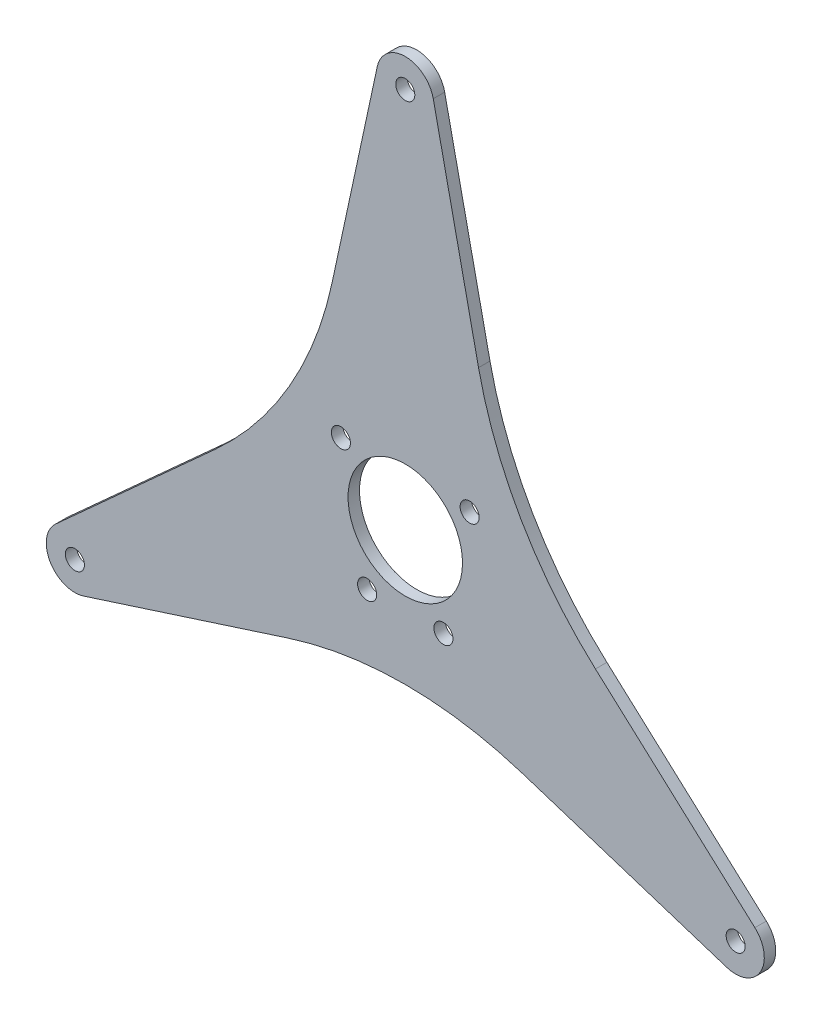
SolidWorks part; units mm, degrees
ref_plane "Front Plane" through (0, 0, 0) normal (0, 0, 1) x (1, 0, 0)
ref_plane "Top Plane" through (0, 0, 0) normal (0, 1, 0) x (1, 0, 0)
ref_plane "Right Plane" through (0, 0, 0) normal (1, 0, 0) x (0, 0, -1)
sketch "Sketch1" plane through (0, 0, 0) normal (0, 0, 1) x (1, 0, 0)
  line L0 (33.75, 25.0611) -> (-33.75, 25.0611) construction
  line L1 (0, 0) -> (0, 51.7411) construction
  line L2 (-183.2723, -88.8801) -> (-99.6909, -13.211)
  line L3 (-38.4044, 92.9404) -> (-14.6637, 203.1585)
  line L4 (14.6637, 203.1585) -> (38.4044, 92.9404)
  line L5 (99.6909, -13.211) -> (183.2723, -88.8801)
  line L6 (0, 0) -> (-81.3002, 46.9387) construction
  line L7 (-168.6086, -114.2784) -> (-61.2865, -79.7293)
  line L8 (61.2865, -79.7293) -> (168.6086, -114.2784)
  line L9 (-33.75, 25.0611) -> (20, -36.9324) construction
  line L10 (-20, -36.9324) -> (20, -36.9324) construction
  line L11 (33.75, 25.0611) -> (-20, -36.9324) construction
  line L12 (0, 0) -> (-20, -36.9324) construction
  circle A0 centre (0, 200) radius 5
  circle A1 centre (173.2051, -100) radius 5
  circle A2 centre (-173.2051, -100) radius 5
  circle A7 centre (0, 0) radius 30
  arc A8 (14.6637, 203.1585) -> (-14.6637, 203.1585) centre (0, 200) ccw
  arc A9 (168.6086, -114.2784) -> (183.2723, -88.8801) centre (173.2051, -100) ccw
  arc A10 (-183.2723, -88.8801) -> (-168.6086, -114.2784) centre (-173.2051, -100) ccw
  arc A11 (38.4044, 92.9404) -> (99.6909, -13.211) centre (233.9202, 135.0539) ccw
  arc A12 (-99.6909, -13.211) -> (-38.4044, 92.9404) centre (-233.9202, 135.0539) ccw
  arc A13 (-61.2865, -79.7293) -> (61.2865, -79.7293) centre (0, -270.1078) cw
  circle A14 centre (0, 0) radius 67 construction
  circle A15 centre (-33.75, 25.0611) radius 5
  circle A16 centre (33.75, 25.0611) radius 5
  circle A17 centre (-20, -36.9324) radius 5
  circle A18 centre (20, -36.9324) radius 5
  point P2 (0, 25.0611)
  point P10 (0, 0)
  point P21 (0, 0)
  point P30 (0, -60)
  point P40 (51.9615, 30)
  point P43 (-51.9615, 30)
  point P51 (0, -36.9324)
  dimension "D1" = 10
  dimension "D4" = 42
  dimension "D8" = 60
  dimension "D9" = 30
  dimension "D11" = 200
  dimension "D12" = 200
  dimension "D15" = 10
  dimension "D2" = 200
  dimension "D10" = 60
  dimension "D13" = 60
  dimension "D14" = 60
  dimension "D16" = 67.5
  dimension "D17" = 40
  dimension "D18" = 63.5
  dimension "D3" = 3
extrude "Boss-Extrude1" add sketch "Sketch1" along normal blind 6
